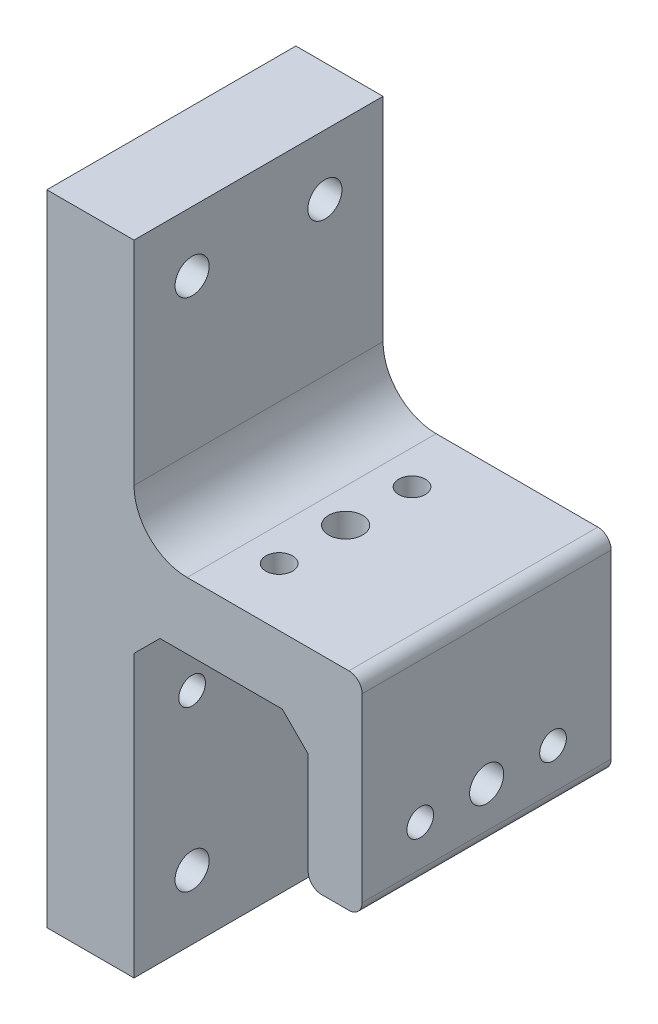
SolidWorks part; units mm, degrees
ref_plane "Front Plane" through (0, 0, 0) normal (0, 0, 1) x (1, 0, 0)
ref_plane "Top Plane" through (0, 0, 0) normal (0, 1, 0) x (1, 0, 0)
ref_plane "Right Plane" through (0, 0, 0) normal (1, 0, 0) x (0, 0, -1)
sketch "Sketch1" plane through (0, 0, 0) normal (0, 0, 1) x (1, 0, 0)
  line L0 (0, -24.9936) -> (0, 24.9936) construction
  line L1 (-20.6248, 0) -> (20.6248, 0) construction
  line L2 (-20.6248, 24.9936) -> (-20.6248, -24.9936) construction
  line L3 (-20.6248, -24.9936) -> (-16.656, -24.9936) construction
  line L4 (-16.656, -24.9936) -> (-16.656, -2.9797) construction
  line L5 (-16.656, -2.9797) -> (-11.6951, 1.9812) construction
  line L6 (-11.6951, 1.9812) -> (11.6951, 1.9812) construction
  line L7 (11.6951, 1.9812) -> (16.656, -2.9797) construction
  line L8 (16.656, -2.9797) -> (16.6561, -24.9936) construction
  line L9 (16.6561, -24.9936) -> (20.6248, -24.9936) construction
  line L10 (20.6248, -24.9936) -> (20.6248, 8.3312) construction
  line L11 (20.6248, 8.3312) -> (-12.6873, 8.3312) construction
  line L12 (-12.6873, 8.3312) -> (-12.6873, 24.9936) construction
  line L13 (-12.6873, 24.9936) -> (-20.6248, 24.9936) construction
  line L14 (-16.6561, -4.3688) -> (-12.8461, -4.3688) construction
  line L15 (-12.8461, -4.3688) -> (-12.8461, -11.5062) construction
  line L16 (-12.8461, -11.5062) -> (-10.306, -11.5062) construction
  line L17 (-10.306, -11.5062) -> (-10.306, -17.8562) construction
  line L18 (-10.306, -17.8562) -> (-12.8461, -17.8562) construction
  line L19 (-12.8461, -17.8562) -> (-12.8461, -24.9936) construction
  line L20 (-12.8461, -24.9936) -> (-16.656, -24.9936) construction
  line L21 (-12.8461, -11.5062) -> (-12.8461, -17.8562) construction
  line L22 (-10.306, -14.6812) -> (-16.656, -14.6812) construction
  line L23 (-16.656, -14.6812) -> (20.6248, -14.6812) construction
  point P4 (0, 0)
  point P7 (0, 0)
  point P30 (0, 1.9812)
  point P31 (0, 5.1562)
  dimension "Length (B)" = 49.9872
  dimension "Length (A)" = 41.2496
  dimension "Mounting Hole Depth" = 7.9375
  dimension "D1" = 3.9688
  dimension "Chamfer" = 4.9609
  dimension "D2" = 45
  dimension "Pad Width" = 20.6248
  dimension "Pad Height" = 6.35
  dimension "Pad Thickness" = 3.81
  dimension "Pad Rail" = 6.35
  dimension "Countersink Depth" = 3.175
  dimension "Inner Height" = 26.9748
  dimension "Length (C)" = 33.3248
sketch "Sketch2" plane through (0, 0, 0) normal (1, 0, 0) x (0, 0, -1)
  line L0 (-23.8125, 0) -> (23.8125, 0) construction
  line L1 (-23.8125, 8.3312) -> (23.8125, 8.3312) construction
  line L2 (-23.8125, 24.9936) -> (23.8125, 24.9936) construction
  line L3 (-23.8125, 24.9936) -> (-23.8125, -24.9936) construction
  line L4 (-23.8125, -24.9936) -> (23.8125, -24.9936) construction
  line L5 (23.8125, 24.9936) -> (23.8125, -24.9936) construction
  line L7 (0, 24.9936) -> (0, 8.3312) construction
  line L8 (-12.7, 16.6624) -> (12.7, 16.6624) construction
  line L9 (-23.8125, -14.6812) -> (23.8125, -14.6812) construction
  line L10 (-13.2105, -17.2339) -> (-12.1895, -17.2339) construction
  line L11 (-13.2105, -17.2339) -> (-13.2105, -12.1285) construction
  line L12 (-13.2105, -12.1285) -> (-12.1895, -12.1285) construction
  line L13 (-12.1895, -17.2339) -> (-12.1895, -12.1285) construction
  line L14 (-12.7, -12.1285) -> (-12.7, -17.2339) construction
  line L15 (-13.2105, -14.6812) -> (-12.1895, -14.6812) construction
  line L16 (-15.2527, -14.1707) -> (-10.1473, -14.1707) construction
  line L17 (-15.2527, -14.1707) -> (-15.2527, -15.1917) construction
  line L18 (-15.2527, -15.1917) -> (-10.1473, -15.1917) construction
  line L19 (-10.1473, -14.1707) -> (-10.1473, -15.1917) construction
  line L20 (-12.7, -15.1917) -> (-12.7, -14.1707) construction
  line L21 (-15.2527, -14.6812) -> (-10.1473, -14.6812) construction
  line L22 (12.7, -12.1285) -> (-12.7, -12.1285) construction
  line L23 (0, -14.6812) -> (0, -12.1285) construction
  circle A0 centre (-12.7, 16.6624) radius 3.2639 construction
  circle A1 centre (12.7, 16.6624) radius 3.2639 construction
  circle A2 centre (0, -14.6812) radius 3.2639 construction
  circle A3 centre (-12.7, -14.6812) radius 2.5527 construction
  circle A4 centre (12.7, -14.6812) radius 2.5527 construction
  circle A5 centre (12.7, -14.6812) radius 1.5875
  circle A6 centre (-12.7, -14.6812) radius 1.5875
  point P12 (0, 8.3312)
  point P16 (0, 16.6624)
  point P22 (0, -14.6812)
  point P42 (0, -14.6812)
  point P44 (0, 16.6624)
  dimension "Mounting Hole Diameter" = 6.5278
  dimension "Hole Diameter 2" = 6.5278
  dimension "D1" = 5.1054
  dimension "Pilot Hole" = 3.175
  dimension "Length" = 47.625
  dimension "Mounting Hole Spacing" = 25.4
  dimension "D2" = 1.0211
sketch "Sketch3" plane through (0, 0, 0) normal (0, 1, 0) x (1, 0, 0)
  line L0 (0, -23.8125) -> (0, 23.8125) construction
  line L1 (0, 12.7) -> (0, -12.7) construction
  line L5 (0, -23.8125) -> (0, 23.8125) construction
  circle A0 centre (0, 12.7) radius 2.5527 construction
  circle A1 centre (0, -12.7) radius 2.5527 construction
  circle A2 centre (0, 0) radius 3.2639 construction
  circle A3 centre (0, 12.7) radius 4.2164 construction
  circle A4 centre (0, -12.7) radius 4.2164 construction
  dimension "D1" = 6.5278
  dimension "D2" = 5.1054
  dimension "Countersink Diameter" = 8.4328
ref_plane "Plane1" through (0, 0, 12.7) normal (0, 0, 1) x (1, 0, 0)
sketch "Sketch11" plane through (0, 0, 12.7) normal (0, 0, 1) x (1, 0, 0)
  line L0 (-16.656, -14.6812) -> (-20.6248, -14.6812) construction
  line L1 (-20.6248, 24.9936) -> (-20.6248, -24.9936) construction
  line L2 (-20.6248, -10.4648) -> (-20.6248, -18.8976) construction
  line L3 (-20.6248, -10.4648) -> (-19.1116, -12.2682) construction
  line L4 (-19.1116, -12.2682) -> (-19.1116, -17.0942) construction
  line L5 (-19.1116, -17.0942) -> (-20.6248, -18.8976) construction
  line L6 (-19.1116, -12.2682) -> (-11.5761, -12.2682) construction
  line L7 (-11.5761, -12.2682) -> (-11.5761, -11.5062) construction
  line L8 (-12.8461, -11.5062) -> (-10.306, -11.5062) construction
  point P7 (-19.8682, -11.3665)
  dimension "D1" = 8.4328
  dimension "D2" = 100
  dimension "D3" = 4.826
sketch "Sketch4" plane through (0, 0, 0) normal (0, 0, 1) x (1, 0, 0)
  line L0 (-20.6248, -24.9936) -> (-16.656, -24.9936) construction
  line L1 (-20.6248, 24.9936) -> (-20.6248, -24.9936) construction
  line L5 (20.6248, -24.9936) -> (20.6248, 8.3312) construction
  line L6 (16.6561, -24.9936) -> (20.6248, -24.9936) construction
  line L7 (16.656, -2.9797) -> (16.6561, -24.9936) construction
  line L8 (11.6951, 1.9812) -> (16.656, -2.9797) construction
  line L9 (-11.6951, 1.9812) -> (11.6951, 1.9812) construction
  line L10 (-16.656, -2.9797) -> (-11.6951, 1.9812) construction
  line L11 (-16.656, -24.9936) -> (-16.656, -2.9797) construction
  line L12 (-20.6248, -24.9936) -> (-16.656, -24.9936)
  line L13 (-20.6248, 8.3312) -> (-20.6248, -24.9936)
  line L16 (20.6248, 8.3312) -> (-20.6248, 8.3312)
  line L17 (20.6248, -24.9936) -> (20.6248, 8.3312)
  line L18 (16.6561, -24.9936) -> (20.6248, -24.9936)
  line L19 (16.656, -2.9797) -> (16.6561, -24.9936)
  line L20 (11.6951, 1.9812) -> (16.656, -2.9797)
  line L21 (-11.6951, 1.9812) -> (11.6951, 1.9812)
  line L22 (-16.656, -2.9797) -> (-11.6951, 1.9812)
  line L23 (-16.656, -24.9936) -> (-16.656, -2.9797)
  point P3 (-20.291, 8.3312)
extrude "Boss-Extrude1" add sketch "Sketch4" along normal up to vertex (23.8125 mm away) and the other way up to vertex (23.8125 mm away) up to point (0, -24.9936, 23.8125) other way up to point (0, 8.3312, -23.8125)
sketch "Sketch6" plane through (0, 0, 0) normal (1, 0, 0) x (0, 0, -1)
  circle A0 centre (-12.7, -14.6812) radius 2.5527 construction
  circle A1 centre (0, -14.6812) radius 3.2639 construction
  circle A2 centre (12.7, -14.6812) radius 2.5527 construction
  circle A3 centre (12.7, 16.6624) radius 3.2639 construction
  circle A4 centre (-12.7, 16.6624) radius 3.2639 construction
  circle A5 centre (-12.7, -14.6812) radius 2.5527
  circle A6 centre (0, -14.6812) radius 3.2639
  circle A7 centre (12.7, -14.6812) radius 2.5527
  circle A8 centre (12.7, 16.6624) radius 3.2639
  circle A9 centre (-12.7, 16.6624) radius 3.2639
extrude "Cut-Extrude1" cut sketch "Sketch6" against normal through all both and the other way through all
sketch "Sketch7" plane through (0, 0, 0) normal (1, 0, 0) x (0, 0, -1)
  line L1 (-3.2639, -17.9451) -> (3.2639, -17.9451)
  line L2 (-3.2639, -17.9451) -> (-3.2639, -11.4173)
  line L3 (-3.2639, -11.4173) -> (3.2639, -11.4173)
  line L4 (3.2639, -17.9451) -> (3.2639, -11.4173)
  line L5 (0, -11.4173) -> (0, -17.9451) construction
  line L6 (-3.2639, -14.6812) -> (3.2639, -14.6812) construction
  circle A0 centre (-12.7, -14.6812) radius 1.5875 construction
  circle A1 centre (-12.7, -14.6812) radius 1.5875
  circle A2 centre (12.7, -14.6812) radius 1.5875 construction
  circle A3 centre (12.7, -14.6812) radius 1.5875
  circle A4 centre (0, -14.6812) radius 3.2639 construction
  point P6 (0, -14.6812)
extrude "Cut-Extrude2" cut sketch "Sketch7" against normal through all
sketch "Sketch8" plane through (0, 8.3312, 0) normal (0, 1, 0) x (1, 0, 0)
  circle A0 centre (0, 12.7) radius 2.5527 construction
  circle A1 centre (0, -12.7) radius 2.5527 construction
  circle A2 centre (0, 12.7) radius 2.5527
  circle A3 centre (0, -12.7) radius 2.5527
extrude "Cut-Extrude3" cut sketch "Sketch8" against normal up to vertex (6.35 mm away) up to point (0, 1.9812, 0)
sketch "Sketch14" plane through (0, 8.3312, 0) normal (0, 1, 0) x (1, 0, 0)
  circle A0 centre (0, 0) radius 3.2639
  circle A1 centre (0, 0) radius 3.2639 construction
extrude "Cut-Extrude6" cut sketch "Sketch14" against normal through all
sketch "Sketch15" plane through (-20.6248, 0, 0) normal (-1, 0, 0) x (0, 0, 1)
  line L4 (3.2639, -17.9451) -> (3.2639, -11.4173)
  line L5 (-3.2639, -17.9451) -> (3.2639, -17.9451)
  line L6 (-3.2639, -11.4173) -> (-3.2639, -17.9451)
  line L7 (3.2639, -11.4173) -> (-3.2639, -11.4173)
  line L8 (3.2639, -17.9451) -> (3.2639, -11.4173)
  line L9 (-3.2639, -17.9451) -> (3.2639, -17.9451)
  line L10 (-3.2639, -11.4173) -> (-3.2639, -17.9451)
  line L11 (3.2639, -11.4173) -> (-3.2639, -11.4173)
  line L12 (23.8125, 8.3312) -> (-23.8125, 8.3312)
  line L13 (-23.8125, 8.3312) -> (-23.8125, -24.9936)
  line L14 (-23.8125, -24.9936) -> (23.8125, -24.9936)
  line L15 (23.8125, -24.9936) -> (23.8125, 8.3312)
  line L16 (23.8125, 8.3312) -> (-23.8125, 8.3312)
  line L17 (-23.8125, 8.3312) -> (-23.8125, -24.9936)
  line L18 (-23.8125, -24.9936) -> (23.8125, -24.9936)
  line L19 (23.8125, -24.9936) -> (23.8125, 8.3312)
  circle A1 centre (12.7, -14.6812) radius 2.5527
  circle A2 centre (12.7, -14.6812) radius 2.5527
  circle A3 centre (-12.7, -14.6812) radius 2.5527
  circle A4 centre (-12.7, -14.6812) radius 2.5527
  dimension "D1" = 0
  dimension "D2" = 0
  dimension "D3" = 0
  dimension "D4" = 0
extrude "Boss-Extrude2" add sketch "Sketch15" along normal blind 6.35
sketch "Sketch16" plane through (20.6248, 0, 0) normal (1, 0, 0) x (0, 0, -1)
  line L4 (-23.8125, -24.9936) -> (23.8125, -24.9936)
  line L5 (23.8125, -24.9936) -> (23.8125, 8.3312)
  line L6 (23.8125, 8.3312) -> (-23.8125, 8.3312)
  line L7 (-23.8125, 8.3312) -> (-23.8125, -24.9936)
  line L8 (-23.8125, -24.9936) -> (23.8125, -24.9936)
  line L9 (23.8125, -24.9936) -> (23.8125, 8.3312)
  line L10 (23.8125, 8.3312) -> (-23.8125, 8.3312)
  line L11 (-23.8125, 8.3312) -> (-23.8125, -24.9936)
  circle A1 centre (-12.7, -14.6812) radius 2.5527
  circle A2 centre (-12.7, -14.6812) radius 2.5527
  circle A3 centre (0, -14.6812) radius 3.2639
  circle A4 centre (0, -14.6812) radius 3.2639
  circle A5 centre (12.7, -14.6812) radius 2.5527
  circle A6 centre (12.7, -14.6812) radius 2.5527
  dimension "D1" = 0
  dimension "D2" = 0
  dimension "D3" = 0
  dimension "D4" = 0
extrude "Boss-Extrude3" add sketch "Sketch16" along normal blind 6.35
sketch "Sketch17" plane through (0, 8.3312, 0) normal (0, 1, 0) x (1, 0, 0)
  line L4 (-26.9748, -23.8125) -> (26.9748, -23.8125)
  line L5 (26.9748, -23.8125) -> (26.9748, 23.8125)
  line L6 (26.9748, 23.8125) -> (-26.9748, 23.8125)
  line L7 (-26.9748, 23.8125) -> (-26.9748, -23.8125)
  line L8 (-26.9748, -23.8125) -> (26.9748, -23.8125)
  line L9 (26.9748, -23.8125) -> (26.9748, 23.8125)
  line L10 (26.9748, 23.8125) -> (-26.9748, 23.8125)
  line L11 (-26.9748, 23.8125) -> (-26.9748, -23.8125)
  circle A1 centre (0, -12.7) radius 2.5527
  circle A2 centre (0, -12.7) radius 2.5527
  circle A3 centre (0, 12.7) radius 2.5527
  circle A4 centre (0, 12.7) radius 2.5527
  circle A5 centre (0, 0) radius 3.2639
  circle A6 centre (0, 0) radius 3.2639
  dimension "D1" = 0
  dimension "D2" = 0
  dimension "D3" = 0
  dimension "D4" = 0
extrude "Boss-Extrude4" add sketch "Sketch17" along normal blind 6.35
sketch "Sketch19" plane through (-26.9748, 0, 0) normal (-1, 0, 0) x (0, 0, 1)
  line L0 (23.8125, -24.9936) -> (23.8125, 14.6812) construction
  line L2 (-23.8125, 14.6812) -> (-23.8125, 65.4812)
  line L3 (-23.8125, 65.4812) -> (23.8125, 65.4812)
  line L4 (23.8125, 14.6812) -> (23.8125, 65.4812)
  line L7 (-23.8125, -24.9936) -> (-23.8125, -56.7436)
  line L8 (-23.8125, -56.7436) -> (23.8125, -56.7436)
  line L9 (-3.2639, -11.4173) -> (-3.2639, -17.9451)
  line L10 (3.2639, -11.4173) -> (-3.2639, -11.4173)
  line L11 (3.2639, -17.9451) -> (3.2639, -11.4173)
  line L12 (-3.2639, -17.9451) -> (3.2639, -17.9451)
  line L13 (-3.2639, -11.4173) -> (-3.2639, -17.9451)
  line L14 (3.2639, -11.4173) -> (-3.2639, -11.4173)
  line L15 (3.2639, -17.9451) -> (3.2639, -11.4173)
  line L16 (-3.2639, -17.9451) -> (3.2639, -17.9451)
  line L17 (23.8125, -24.9936) -> (23.8125, 14.6812)
  line L18 (23.8125, 14.6812) -> (-23.8125, 14.6812)
  line L19 (-23.8125, 14.6812) -> (-23.8125, -24.9936)
  line L20 (-23.8125, -24.9936) -> (23.8125, -24.9936)
  line L21 (23.8125, -24.9936) -> (23.8125, 14.6812)
  line L23 (-23.8125, 14.6812) -> (-23.8125, -24.9936)
  line L25 (23.8125, -24.9936) -> (23.8125, -56.7436)
  circle A1 centre (12.7, -14.6812) radius 2.5527
  circle A2 centre (12.7, -14.6812) radius 2.5527
  circle A3 centre (-12.7, -14.6812) radius 2.5527
  circle A4 centre (-12.7, -14.6812) radius 2.5527
  dimension "D1" = 50.8
  dimension "D6" = 31.75
  dimension "D2" = 0
  dimension "D3" = 0
  dimension "D4" = 0
  dimension "D5" = 0
extrude "Boss-Extrude5" add sketch "Sketch19" along normal blind 6.35 and the other way up to surface (10.3187 mm away) other way up to face at (-16.656, -14.6812, -10.1473)
fillet "Fillet2" radius 10.16 1 edges at (-16.6561, 14.6812, 0)
fillet "Fillet3" radius 2.54 3 edges at (16.6561, -24.9936, 0) (26.9748, -24.9936, 0) (26.9748, 14.6812, 0)
sketch "Sketch20" plane through (-33.3248, 0, 0) normal (-1, 0, 0) x (0, 0, 1)
  line L0 (-12.7, 53.975) -> (0, 0) construction
  line L1 (-12.7, -44.45) -> (12.7, -44.45) construction
  line L2 (-12.7, -44.45) -> (-12.7, 53.975) construction
  line L3 (-12.7, 53.975) -> (12.7, 53.975) construction
  line L4 (12.7, -44.45) -> (12.7, 53.975) construction
  line L5 (0, 0) -> (12.7, 53.975) construction
  circle A0 centre (-12.7, 53.975) radius 3.2639
  circle A1 centre (-12.7, -44.45) radius 3.2639
  circle A2 centre (12.7, 53.975) radius 3.2639
  circle A3 centre (12.7, -44.45) radius 3.2639
  point P4 (0, 0)
  dimension "D1" = 6.5278
  dimension "D2" = 25.4
  dimension "D3" = 53.975
  dimension "D4" = 44.45
extrude "Cut-Extrude7" cut sketch "Sketch20" against normal through all
equation "\"D1@Sketch1\" = \"Mounting Hole Depth@Sketch1\" / 2"
equation "\"D1@Sketch3\"=\"Hole Diameter 2@Sketch2\""
equation "\"D2@Sketch3\"=\"D1@Sketch2\""
equation "\"D2@Sketch2\"=\"D1@Sketch2\"*.2"
equation "\"D1@Sketch11\"=\"Countersink Diameter@Sketch3\""
equation "\"Chamfer@Sketch1\"=\"Mounting Hole Depth@Sketch1\"*.625"
